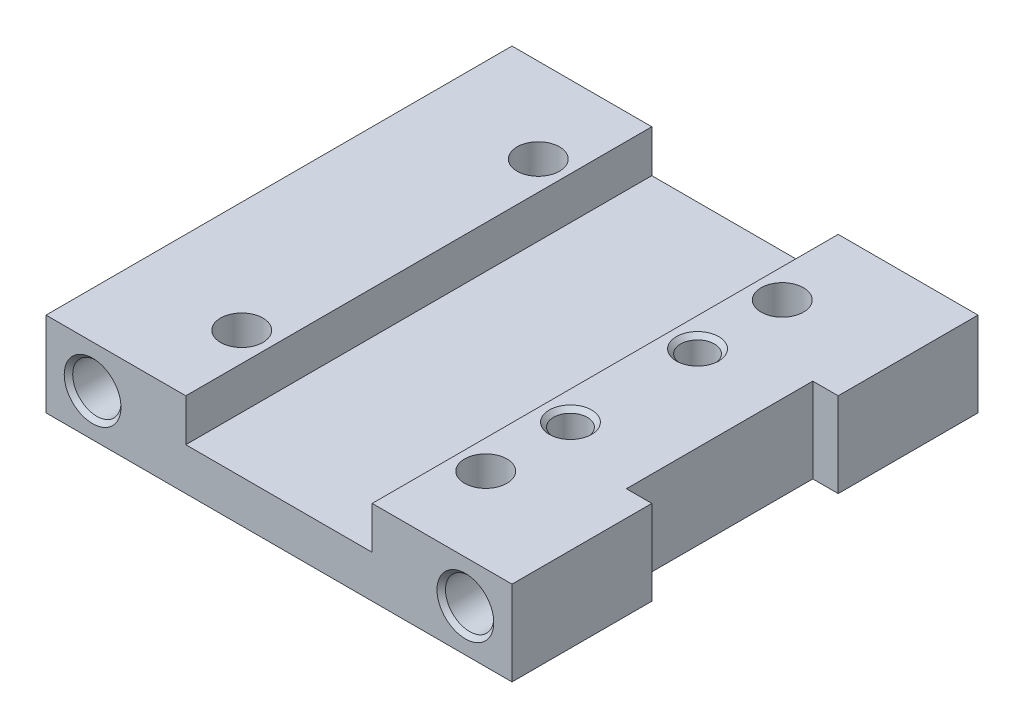
SolidWorks part; units mm, degrees
material "ABS PC"
ref_plane "Front Plane" through (0, 0, 0) normal (0, 0, 1) x (1, 0, 0)
ref_plane "Top Plane" through (0, 0, 0) normal (0, 1, 0) x (1, 0, 0)
ref_plane "Right Plane" through (0, 0, 0) normal (1, 0, 0) x (0, 0, -1)
sketch "Sketch1" plane through (0, 0, 0) normal (0, 1, 0) x (1, 0, 0)
  line L0 (14.4, 11) -> (14.4, -11) construction
  line L1 (-27.5, 27.5) -> (27.5, 27.5)
  line L2 (-27.5, 27.5) -> (-27.5, -27.5)
  line L3 (-27.5, -27.5) -> (27.5, -27.5)
  line L4 (27.5, 27.5) -> (27.5, -27.5)
  line L5 (-27.5, 27.5) -> (27.5, -27.5) construction
  line L6 (-27.5, -27.5) -> (27.5, 27.5) construction
  line L7 (27.5, 11) -> (24.5, 11)
  line L8 (27.5, 11) -> (27.5, -11)
  line L9 (27.5, -11) -> (24.5, -11)
  line L10 (24.5, 11) -> (24.5, -11)
  line L11 (27.5, 11) -> (24.5, -11) construction
  line L12 (27.5, -11) -> (24.5, 11) construction
  line L13 (0, -4.867) -> (0, 6.9347) construction
  circle A0 centre (14.4, 7.5) radius 2
  circle A1 centre (14.4, -7.5) radius 2
  circle A2 centre (14.4, 17.5) radius 2.5
  circle A3 centre (14.4, -17.5) radius 2.5
  circle A4 centre (-14.4, -17.5) radius 2.5
  circle A5 centre (-14.4, 17.5) radius 2.5
  point P0 (0, 0)
  point P14 (26, 0)
  point P23 (0, 0)
  dimension "D6" = 3.5
  dimension "D8" = 4
  dimension "D13" = 5
  dimension "D1" = 55
  dimension "D2" = 55
  dimension "D3" = 22
  dimension "D4" = 3
  dimension "D5" = 13.1
  dimension "D7" = 3.5
  dimension "D9" = 22
  dimension "D11" = 10
  dimension "D12" = 10
extrude "Boss-Extrude1" add sketch "Sketch1" along normal mid plane 10 contours L10 L7 L4 L1 L2 L3 L9 A4 A3 A2 A1 A0 A5
sketch "Sketch2" plane through (0, 0, 27.5) normal (0, 0, 1) x (1, 0, 0)
  line L0 (0, 5) -> (0, -5) construction
  line L1 (-27.5, 5) -> (27.5, 5) construction
  line L2 (-27.5, -5) -> (27.5, -5) construction
  circle A0 centre (-22, 0) radius 2.85
  circle A1 centre (22, 0) radius 2.85
  dimension "D1" = 22
  dimension "D2" = 5.7
extrude "Cut-Extrude1" cut sketch "Sketch2" against normal blind 8
mirror "Mirror1" about plane through (0, 0, 0) normal (0, 0, 1) of "Cut-Extrude1"
chamfer "Chamfer1" distance 0.5 angle 45 6 edges at (14.4, 5, 9.5) (14.4, 5, -5.5) (-19.15, 0, -27.5) (19.15, 0, -27.5) (19.15, 0, 27.5) (-19.15, 0, 27.5)
sketch "Sketch3" plane through (0, 5, 0) normal (0, 1, 0) x (1, 0, 0)
  line L0 (-27.5, -27.5) -> (27.5, -27.5) construction
  line L1 (-11, 27.5) -> (11, 27.5)
  line L2 (-11, 27.5) -> (-11, -27.5)
  line L3 (-11, -27.5) -> (11, -27.5)
  line L4 (11, 27.5) -> (11, -27.5)
  line L5 (-11, 27.5) -> (11, -27.5) construction
  line L6 (-11, -27.5) -> (11, 27.5) construction
  point P0 (0, 0)
  dimension "D1" = 22
extrude "Cut-Extrude2" cut sketch "Sketch3" against normal blind 5
